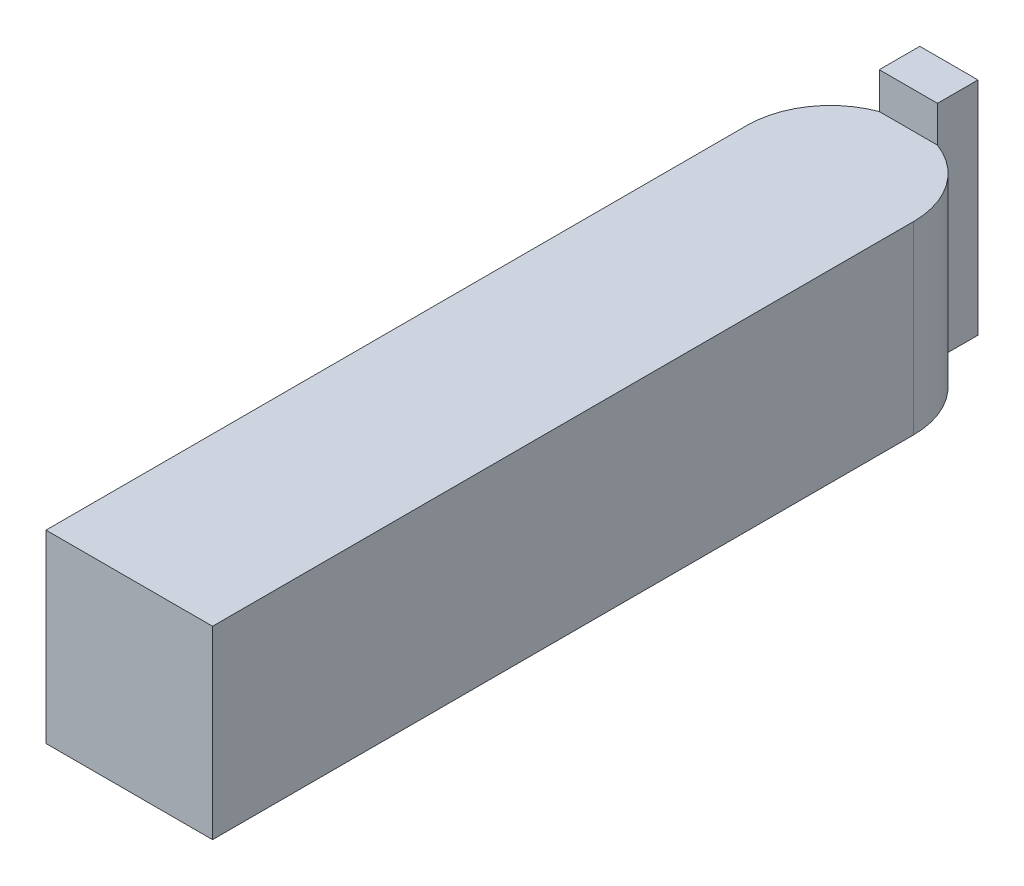
SolidWorks part; units mm, degrees
ref_plane "Front Plane" through (0, 0, 0) normal (0, 0, 1) x (1, 0, 0)
ref_plane "Top Plane" through (0, 0, 0) normal (0, 1, 0) x (1, 0, 0)
ref_plane "Right Plane" through (0, 0, 0) normal (1, 0, 0) x (0, 0, -1)
sketch "Sketch1" plane through (0, 0, 0) normal (0, 1, 0) x (1, 0, 0)
  line L0 (5.75, 85.695) -> (-5.75, 85.695) construction
  line L1 (-16.45, -69.245) -> (16.45, -69.245)
  line L2 (-16.45, -69.245) -> (-16.45, 69.245)
  line L4 (16.45, -69.245) -> (16.45, 69.245)
  line L5 (-16.45, -69.245) -> (16.45, 69.245) construction
  line L6 (-16.45, 69.245) -> (16.45, -69.245) construction
  line L7 (-5.75, 84.6573) -> (-5.75, 92.6573)
  line L8 (-5.75, 92.6573) -> (5.75, 92.6573)
  line L9 (5.75, 92.6573) -> (5.75, 84.6573)
  line L10 (0, 85.695) -> (0, 92.6573) construction
  line L11 (5.75, 84.6573) -> (-5.75, 84.6573) construction
  arc A0 (-16.45, 69.245) -> (-5.75, 84.6573) centre (0, 69.245) cw
  arc A1 (5.75, 84.6573) -> (16.45, 69.245) centre (0, 69.245) cw
  arc A2 (-5.75, 84.6573) -> (5.75, 84.6573) centre (0, 69.245) cw construction
  point P0 (0, 0)
  point P11 (0, 85.695)
  point P17 (-5.75, 85.695)
  point P18 (5.75, 85.695)
  dimension "D1" = 32.9
  dimension "D2" = 154.94
  dimension "D3" = 8
  dimension "D4" = 11.5
extrude "Boss-Extrude1" add sketch "Sketch1" along normal blind 36.5125
sketch "Sketch2" plane through (0, 36.5125, 0) normal (0, 1, 0) x (1, 0, 0)
  line L0 (-5.75, 84.6573) -> (5.75, 84.6573)
  line L1 (5.75, 84.6573) -> (5.75, 92.6573)
  line L2 (5.75, 92.6573) -> (-5.75, 92.6573)
  line L3 (-5.75, 92.6573) -> (-5.75, 84.6573)
extrude "Boss-Extrude2" add sketch "Sketch2" along normal blind 7.16
